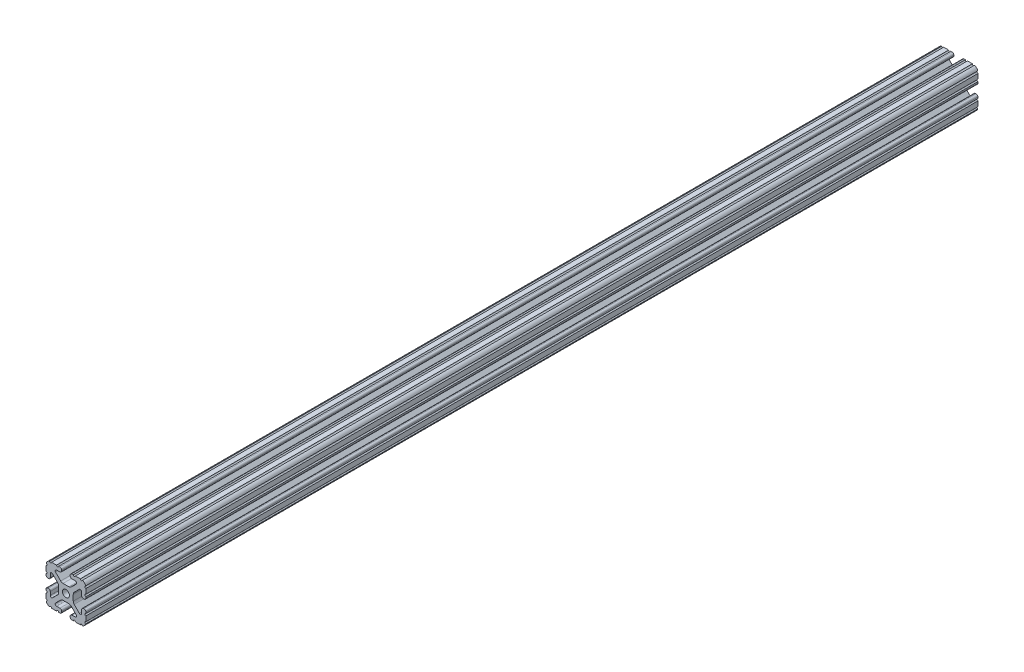
SolidWorks part; units mm, degrees
ref_plane "Front Plane" through (0, 0, 0) normal (0, 0, 1) x (1, 0, 0)
ref_plane "Top Plane" through (0, 0, 0) normal (0, 1, 0) x (1, 0, 0)
ref_plane "Right Plane" through (0, 0, 0) normal (1, 0, 0) x (0, 0, -1)
sketch "Sketch2" plane through (0, 0, 0) normal (0, 0, 1) x (1, 0, 0)
  line L0 (0, 19.05) -> (0, -19.05) construction
  line L1 (-19.05, 0) -> (19.05, 0) construction
  line L2 (4.064, -19.05) -> (19.05, -19.05)
  line L3 (19.05, -19.05) -> (19.05, -4.064)
  line L4 (4.064, -19.05) -> (4.064, -14.986)
  line L5 (4.064, -14.986) -> (12.1123, -14.986)
  line L6 (12.1123, -14.986) -> (4.1113, -6.985)
  line L7 (0, 0) -> (19.05, -19.05) construction
  line L8 (19.05, -4.064) -> (14.986, -4.064)
  line L9 (14.986, -4.064) -> (14.986, -12.1123)
  line L10 (14.986, -12.1123) -> (6.985, -4.1113)
  circle A0 centre (0, 0) radius 3.3274
  arc A1 (8.9963, -14.986) -> (9.909, -12.7826) centre (8.9963, -13.6953) ccw construction
  point P8 (0, -6.985)
  dimension "Center Hole Diameter" = 6.6548
  dimension "Rail Height" = 38.1
  dimension "Rail Width" = 38.1
  dimension "T-Slot Width" = 8.128
  dimension "Slot Inner Width" = 20.574
  dimension "Thickness" = 4.064
  dimension "Slot Depth" = 8.001
  dimension "D1" = 4.064
sketch "Sketch3" plane through (0, 0, 0) normal (1, 0, 0) x (0, 0, -1)
  line L0 (-426.2, -19.05) -> (426.2, -19.05) construction
  line L1 (-400.8, 0) -> (400.8, 0) construction
  dimension "Length" = 852.4
  dimension "D1" = 25.4
sketch "Sketch4" plane through (0, 0, 0) normal (0, 0, 1) x (1, 0, 0)
  line L0 (5.7912, -19.05) -> (14.3002, -19.05)
  line L1 (4.064, -19.05) -> (19.05, -19.05) construction
  line L2 (4.064, -19.05) -> (4.064, -14.986) construction
  line L3 (4.064, -14.986) -> (12.1123, -14.986) construction
  line L4 (4.064, -16.7132) -> (4.064, -17.3228)
  line L5 (5.7912, -14.986) -> (8.9963, -14.986)
  line L6 (0, -6.985) -> (2.833, -6.985)
  line L7 (12.1123, -14.986) -> (4.1113, -6.985) construction
  line L8 (5.0152, -7.8889) -> (9.909, -12.7826)
  line L9 (19.05, -19.05) -> (19.05, -4.064) construction
  line L10 (14.986, -12.1123) -> (6.985, -4.1113) construction
  line L11 (14.986, -4.064) -> (14.986, -12.1123) construction
  line L12 (14.986, -8.9963) -> (14.986, -5.7912)
  line L13 (19.05, -4.064) -> (14.986, -4.064) construction
  line L14 (16.7132, -4.064) -> (17.3228, -4.064)
  line L15 (19.05, -5.7912) -> (19.05, -14.3002)
  line L16 (12.7826, -9.909) -> (7.8889, -5.0152)
  line L17 (6.985, 0) -> (6.985, -2.833)
  line L18 (-19.05, 0) -> (19.05, 0) construction
  line L19 (0, -6.985) -> (0, -3.3274)
  line L20 (0, 19.05) -> (0, -19.05) construction
  line L21 (6.985, 0) -> (3.3274, 0)
  arc A0 (4.064, -17.3228) -> (5.7912, -19.05) centre (5.7912, -17.3228) ccw
  arc A2 (4.064, -16.7132) -> (5.7912, -14.986) centre (5.7912, -16.7132) cw
  arc A3 (8.9963, -14.986) -> (9.909, -12.7826) centre (8.9963, -13.6953) ccw
  arc A4 (2.833, -6.985) -> (5.0152, -7.8889) centre (2.833, -10.0711) cw
  arc A5 (14.3002, -19.05) -> (19.05, -14.3002) centre (14.3002, -14.3002) ccw
  arc A6 (12.7826, -9.909) -> (14.986, -8.9963) centre (13.6953, -8.9963) ccw
  arc A7 (14.986, -5.7912) -> (16.7132, -4.064) centre (16.7132, -5.7912) cw
  arc A8 (17.3228, -4.064) -> (19.05, -5.7912) centre (17.3228, -5.7912) cw
  arc A9 (7.8889, -5.0152) -> (6.985, -2.833) centre (10.0711, -2.833) cw
  circle A10 centre (0, 0) radius 3.3274 construction
  arc A11 (0, -3.3274) -> (3.3274, 0) centre (0, 0) ccw
  dimension "D1" = 4.7498
  dimension "D2" = 3.0861
  dimension "D3" = 1.7272
extrude "Boss-Extrude1" add sketch "Sketch4" along normal mid plane 852.4
sketch "Sketch5" plane through (0, 0, 0) normal (0, 0, 1) x (1, 0, 0)
  line L0 (4.064, -19.05) -> (19.05, -19.05) construction
  line L1 (5.7912, -14.986) -> (8.9963, -14.986) construction
  line L3 (0, 0) -> (19.05, -19.05) construction
  line L4 (8.9963, -14.986) -> (8.9963, -19.05) construction
  line L5 (12.1123, -14.986) -> (4.1113, -6.985) construction
  circle A0 centre (14.7395, -19.05) radius 1.016
  circle A1 centre (7.9803, -19.05) radius 1.016
  circle A2 centre (19.05, -14.7395) radius 1.016
  circle A3 centre (19.05, -7.9803) radius 1.016
  point P10 (7.3938, -14.986)
  point P12 (13.6953, -8.9963)
  dimension "D1" = 2.032
extrude "Cut-Extrude1" cut sketch "Sketch5" against normal through all both and the other way through all
mirror "Mirror1" about plane through (0, 0, 0) normal (1, 0, 0) of bodies 137 134
mirror "Mirror2" about plane through (0, 0, 0) normal (0, 1, 0) of bodies 135
equation "\"D1@Boss-Extrude1\"=\"Length@Sketch3\""
equation "\"D1@Sketch2\"=\"Thickness@Sketch2\""
equation "\"D2@Sketch4\"=\"Slot Inner Width@Sketch2\"*0.15"
equation "\"D1@Sketch4\"=\"D3@Sketch4\"*2.75"
equation "\"D3@Sketch4\"=\"Thickness@Sketch2\"*0.425"
equation "\"D1@Sketch5\"=\"Thickness@Sketch2\"*0.5"
